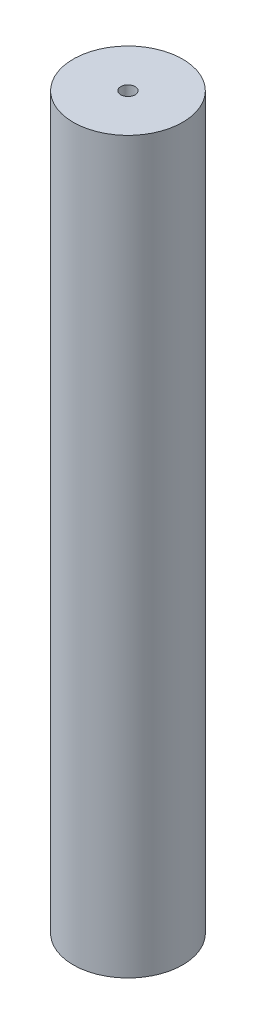
SolidWorks part; units mm, degrees
material "6061-T6"
ref_plane "Front" through (0, 0, 0) normal (0, 0, 1) x (1, 0, 0)
ref_plane "Top" through (0, 0, 0) normal (0, 1, 0) x (1, 0, 0)
ref_plane "Right" through (0, 0, 0) normal (1, 0, 0) x (0, 0, -1)
sketch "Sketch1" plane through (0, 0, 0) normal (0, 1, 0) x (1, 0, 0)
  circle A0 centre (0, 0) radius 19.05
  dimension "D1" = 38.1
extrude "Boss-Extrude1" add sketch "Sketch1" along normal mid plane 254
hole_wizard "M6x1.0 Tapped Hole1" positions "Sketch2" profile "Sketch3" tap size "M6x1.0" standard "ANSI Metric"
sketch "Sketch2" plane through (0, 127, 0) normal (0, 1, 0) x (1, 0, 0)
  point P0 (0, 0)
sketch "Sketch3" plane through (0, 127, 0) normal (1, 0, 0) x (0, 0, 1)
  line L0 (0, 0) -> (0, 16.5022)
  line L1 (0, 16.5022) -> (2.5, 15)
  line L2 (2.5, 15) -> (2.5, 0)
  line L5 (2.5, 0) -> (0, 0)
  line L10 (0, 16.5022) -> (-2.5, 15) construction
  line L11 (0, -6.35) -> (0, 107.95) construction
  dimension "Tap Drill Dia." = 5
  dimension "Tap Drill Depth" = 15
  dimension "Drill Angle" = 118
cosmetic thread "Hole Thread1" parameters "D1"=12, "D2"=6
